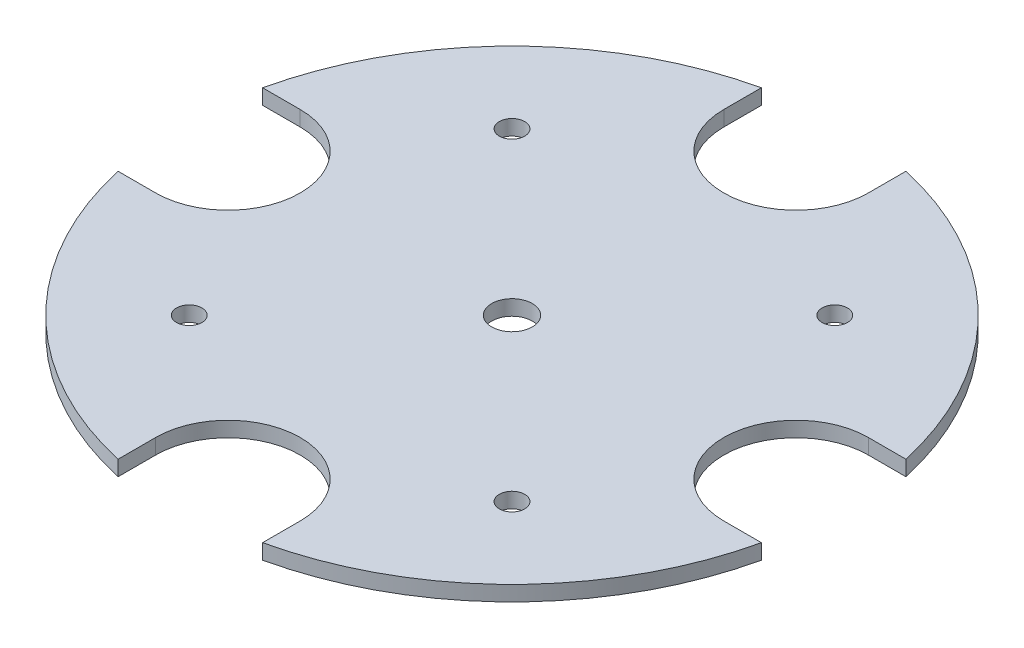
SolidWorks part; units mm, degrees
ref_plane "Front Plane" through (0, 0, 0) normal (0, 0, 1) x (1, 0, 0)
ref_plane "Top Plane" through (0, 0, 0) normal (0, 1, 0) x (1, 0, 0)
ref_plane "Right Plane" through (0, 0, 0) normal (1, 0, 0) x (0, 0, -1)
sketch "Sketch1" plane through (0, 0, 0) normal (0, 1, 0) x (1, 0, 0)
  line L1 (-56, 14.25) -> (-63.4187, 14.25)
  line L2 (-56, -14.25) -> (-63.4187, -14.25)
  line L3 (14.25, 56) -> (14.25, 63.4187)
  line L4 (-14.25, 56) -> (-14.25, 63.4187)
  line L5 (56, -14.25) -> (63.4187, -14.25)
  line L6 (56, 14.25) -> (63.4187, 14.25)
  line L7 (-14.25, -56) -> (-14.25, -63.4187)
  line L8 (14.25, -56) -> (14.25, -63.4187)
  arc A0 (-63.4187, -14.25) -> (-14.25, -63.4187) centre (0, 0) ccw
  arc A1 (-56, -14.25) -> (-56, 14.25) centre (-56, 0) ccw
  arc A2 (-14.25, 56) -> (14.25, 56) centre (0, 56) ccw
  arc A3 (56, 14.25) -> (56, -14.25) centre (56, 0) ccw
  arc A4 (14.25, -56) -> (-14.25, -56) centre (0, -56) ccw
  arc A5 (-14.25, 63.4187) -> (-63.4187, 14.25) centre (0, 0) ccw
  arc A6 (63.4187, 14.25) -> (14.25, 63.4187) centre (0, 0) ccw
  arc A7 (14.25, -63.4187) -> (63.4187, -14.25) centre (0, 0) ccw
  circle A8 centre (-31.8198, 31.8198) radius 2.5
  circle A9 centre (31.8198, 31.8198) radius 2.5
  circle A10 centre (31.8198, -31.8198) radius 2.5
  circle A11 centre (-31.8198, -31.8198) radius 2.5
  circle A12 centre (0, 0) radius 4
  point P26 (0, 0)
  point P36 (0, 0)
  dimension "D1" = 130
  dimension "D3" = 28.5
  dimension "D5" = 5
  dimension "D8" = 8
  dimension "D6" = 45
  dimension "D4" = 4
  dimension "D7" = 4
extrude "Boss-Extrude1" add sketch "Sketch1" along normal blind 3
